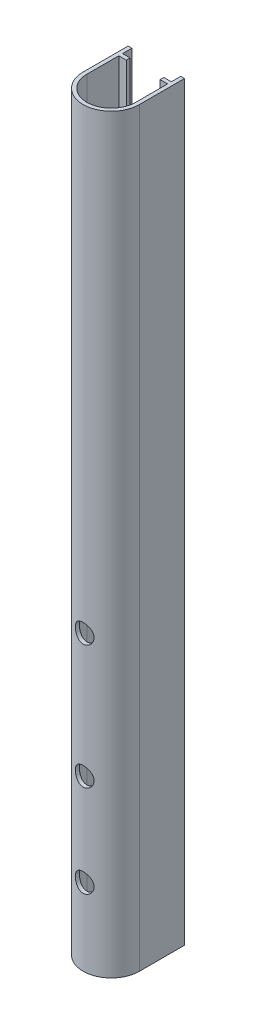
SolidWorks part; units mm, degrees
material "201 Acier inoxydable recuit (SS)"
ref_plane "Plan de face" through (0, 0, 0) normal (0, 0, 1) x (1, 0, 0)
ref_plane "Plan de dessus" through (0, 0, 0) normal (0, 1, 0) x (1, 0, 0)
ref_plane "Plan de droite" through (0, 0, 0) normal (1, 0, 0) x (0, 0, -1)
sketch "Esquisse1" plane through (0, 0, 0) normal (0, 1, 0) x (1, 0, 0)
  line L1 (-7.5, 0) -> (7.5, 0)
  line L2 (-7.5, 0) -> (-7.5, -12)
  line L4 (7.5, 0) -> (7.5, -12)
  arc A0 (-7.5, -12) -> (7.5, -12) centre (0, -12) ccw
  point P5 (0, 0)
  dimension "D2" = 12
  dimension "D1" = 15
extrude "Boss.-Extru.1" add sketch "Esquisse1" along normal blind 200
sketch "Esquisse2" plane through (0, 200, 0) normal (0, 1, 0) x (1, 0, 0)
  line L0 (-6.5, 2.5) -> (6.5, -2.5) construction
  line L1 (-6.5, 2.5) -> (6.5, 2.5)
  line L2 (-6.5, 2.5) -> (-6.5, -2.5)
  line L3 (-6.5, -2.5) -> (-4.5, -2.5)
  line L4 (6.5, 2.5) -> (6.5, -2.5)
  line L5 (6.5, 2.5) -> (-6.5, -2.5) construction
  line L6 (4.5, -2.5) -> (6.5, -2.5)
  line L7 (-6.5, -3.5) -> (-4.5, -3.5)
  line L8 (-6.5, -3.5) -> (-6.5, -12)
  line L10 (6.5, -3.5) -> (6.5, -12)
  line L12 (-4.5, -2.5) -> (-4.5, -3.5)
  line L14 (4.5, -2.5) -> (4.5, -3.5)
  line L15 (4.5, -3.5) -> (6.5, -3.5)
  arc A0 (-6.5, -12) -> (6.5, -12) centre (0, -12) ccw
  arc A1 (-7.5, -12) -> (7.5, -12) centre (0, -12) ccw construction
  point P4 (0, 0)
  point P18 (-5.5, -3.5)
  dimension "D1" = 13
  dimension "D2" = 2.5
  dimension "D3" = 1
  dimension "D4" = 2
extrude "Enlèv. mat.-Extru.1" cut sketch "Esquisse2" against normal through all contours L1 L4 L6 L14 L15 L10 A0 L8 L7 L12 L3 L2
sketch "Esquisse6" plane through (0, 0, 0) normal (0, 0, 1) x (1, 0, 0)
  line L0 (-7.5, 0) -> (7.5, 0) construction
  circle A0 centre (0, 20.5) radius 2.5
  circle A1 centre (0, 45) radius 2.5
  circle A2 centre (0, 78) radius 2.5
  dimension "D4" = 5
  dimension "D1" = 20.5
  dimension "D2" = 45
  dimension "D3" = 78
extrude "Enlèv. mat.-Extru.3" cut sketch "Esquisse6" along normal through all
